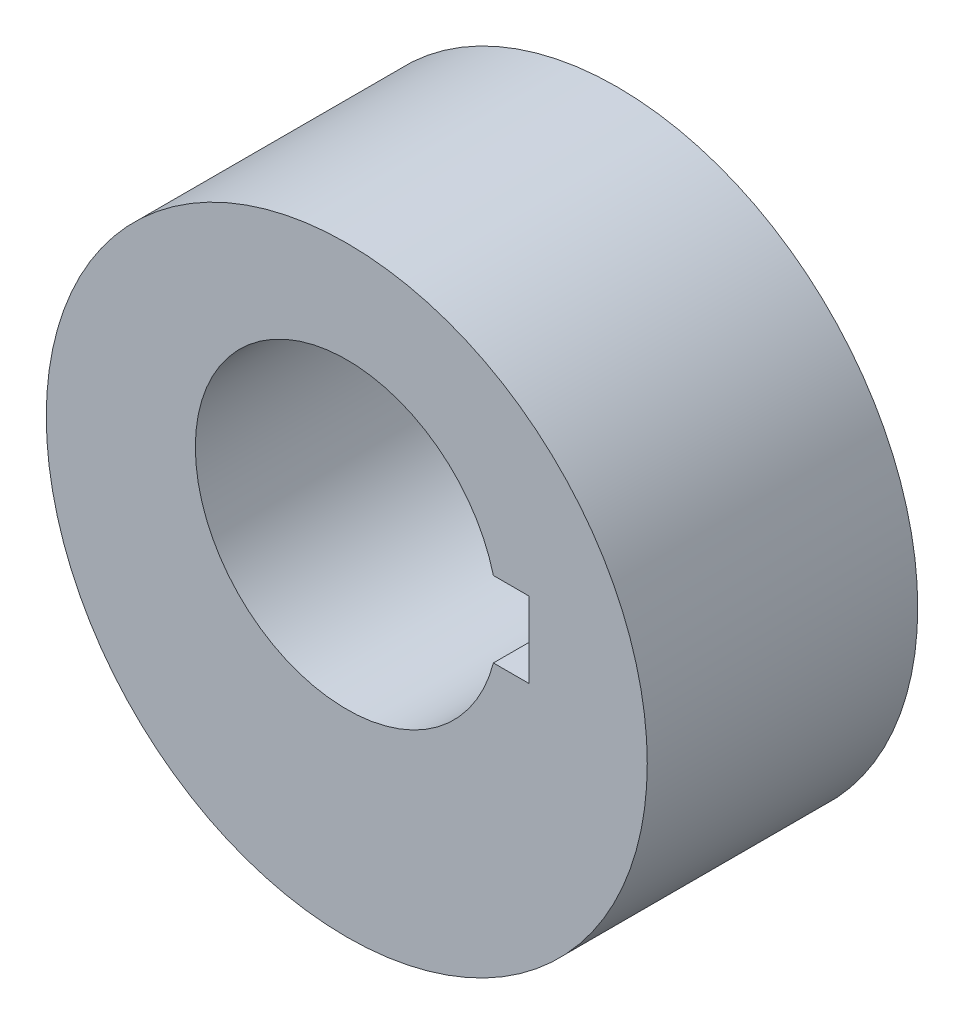
SolidWorks part; units mm, degrees
ref_plane "Front Plane" through (0, 0, 0) normal (0, 0, 1) x (1, 0, 0)
ref_plane "Top Plane" through (0, 0, 0) normal (0, 1, 0) x (1, 0, 0)
ref_plane "Right Plane" through (0, 0, 0) normal (1, 0, 0) x (0, 0, -1)
sketch "Sketch1" plane through (0, 0, 0) normal (0, 0, 1) x (1, 0, 0)
  circle A0 centre (0, 0) radius 7.9375
  circle A1 centre (0, 1.27) radius 4
  dimension "D1" = 15.875
  dimension "D3" = 8
  dimension "D2" = 1.27
extrude "Boss-Extrude1" add sketch "Sketch1" along normal blind 7.1437
ref_plane "Plane2" through (4, 0, 0) normal (-1, 0, 0) x (0, 0, 1)
sketch "Sketch8" plane through (0, 0, 0) normal (0, 0, -1) x (-1, 0, 0)
  line L1 (-4, -3.4925) -> (-4, 3.4925) construction
  line L3 (-4, 0.27) -> (-4.8095, 0.27)
  line L4 (0, 5.27) -> (0, -2.73) construction
  line L5 (0, 1.27) -> (-4, 1.27) construction
  line L6 (-4.8095, 0.27) -> (-4.8095, 2.27)
  line L7 (-4.8095, 2.27) -> (-4, 2.27)
  line L8 (-4, 0.27) -> (-3.873, 0.27)
  line L9 (-4, 2.27) -> (-3.873, 2.27)
  line L10 (-3.873, 2.27) -> (-3.873, 0.27)
  circle A0 centre (0, 1.27) radius 4 construction
  dimension "D1" = 1
  dimension "D2" = 1
  dimension "D3" = 0.8095
extrude "Cut-Extrude2" cut sketch "Sketch8" against normal through all
